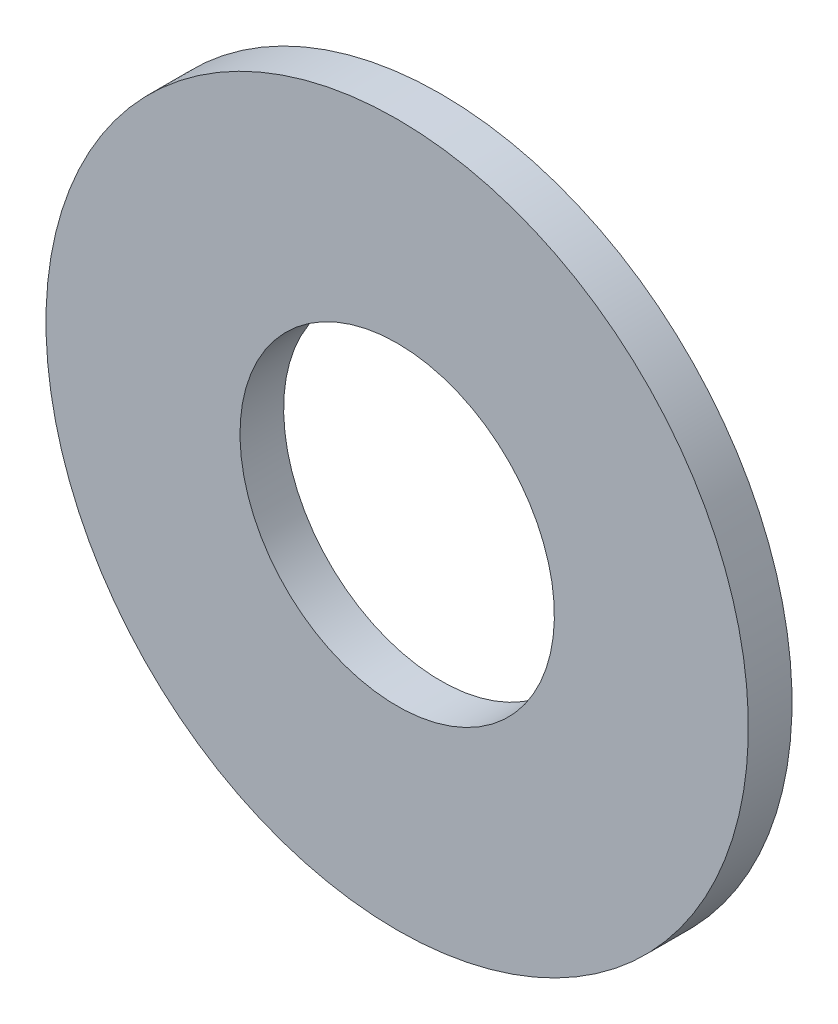
SolidWorks part; units mm, degrees
material "ASTM A36 Steel"
ref_plane "Front Plane" through (0, 0, 0) normal (0, 0, 1) x (1, 0, 0)
ref_plane "Top Plane" through (0, 0, 0) normal (0, 1, 0) x (1, 0, 0)
ref_plane "Right Plane" through (0, 0, 0) normal (1, 0, 0) x (0, 0, -1)
sketch "Sketch2" plane through (0, 0, 0) normal (1, 0, 0) x (0, 0, -1)
  line L0 (-0.889, 0) -> (-4.8387, 0) construction
  line L1 (-0.889, 7.1501) -> (0, 7.1501)
  line L2 (-0.889, 7.1501) -> (-0.889, 3.2004)
  line L3 (-0.889, 3.2004) -> (0, 3.2004)
  line L4 (0, 7.1501) -> (0, 3.2004)
  dimension "D1" = 6.4008
  dimension "D2" = 0.889
  dimension "D3" = 14.3002
revolve "Revolve1" add sketch "Sketch2" angle 360 about L0
